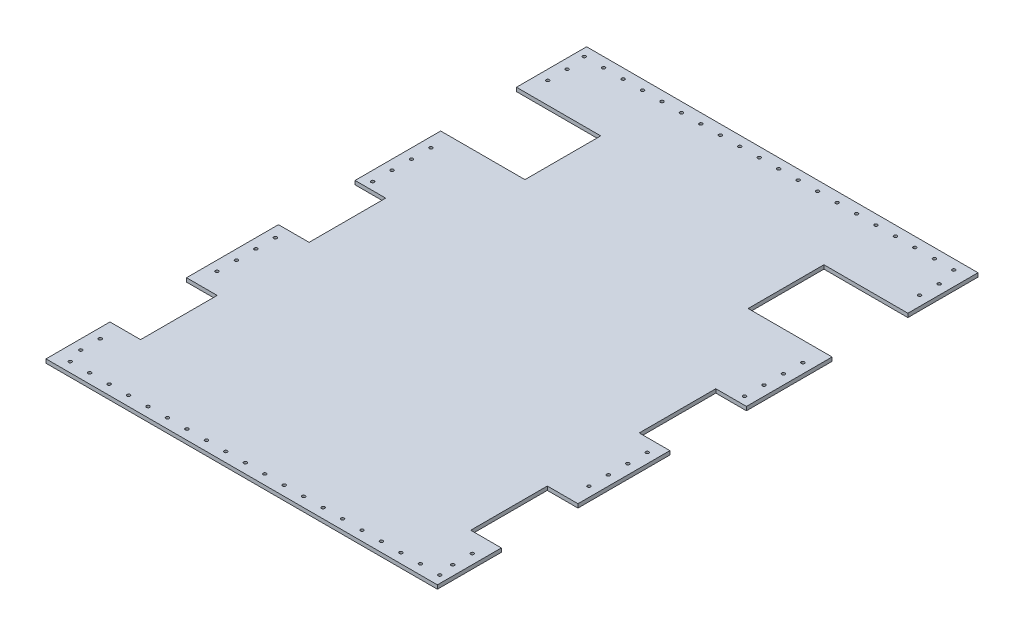
SolidWorks part; units mm, degrees
ref_plane "Alzado" through (0, 0, 0) normal (0, 0, 1) x (1, 0, 0)
ref_plane "Planta" through (0, 0, 0) normal (0, 1, 0) x (1, 0, 0)
ref_plane "Vista lateral" through (0, 0, 0) normal (1, 0, 0) x (0, 0, -1)
sketch "Croquis1" plane through (0, 0, 0) normal (0, 1, 0) x (1, 0, 0)
  line L1 (255.5, 352.9) -> (-255.5, 352.9)
  line L2 (255.5, 352.9) -> (255.5, -352.9)
  line L3 (255.5, -352.9) -> (-255.5, -352.9)
  line L4 (-255.5, 352.9) -> (-255.5, -352.9)
  line L5 (255.5, 352.9) -> (-255.5, -352.9) construction
  line L6 (255.5, -352.9) -> (-255.5, 352.9) construction
  point P0 (0, 0)
  dimension "D1" = 511
  dimension "D2" = 705.8
extrude "Saliente-Extruir1" add sketch "Croquis1" along normal blind 5
sketch "Croquis2" plane through (0, 0, 0) normal (0, -1, 0) x (-1, 0, 0)
  line L0 (255.5, 352.9) -> (255.5, -352.9) construction
  line L1 (255.5, -269.4013) -> (215.5, -269.4013)
  line L2 (255.5, -269.4013) -> (255.5, -169.4013)
  line L3 (255.5, -169.4013) -> (215.5, -169.4013)
  line L4 (215.5, -269.4013) -> (215.5, -169.4013)
  line L5 (-215.5, -269.4013) -> (-215.5, -169.4013)
  line L6 (-215.5, -269.4013) -> (-255.5, -269.4013)
  line L7 (-255.5, -269.4013) -> (-255.5, -169.4013)
  line L8 (-215.5, -169.4013) -> (-255.5, -169.4013)
  line L9 (255.5, -49.4013) -> (255.5, 50.5987)
  line L10 (255.5, -49.4013) -> (215.5, -49.4013)
  line L11 (215.5, -49.4013) -> (215.5, 50.5987)
  line L12 (255.5, 50.5987) -> (215.5, 50.5987)
  line L13 (-215.5, -49.4013) -> (-215.5, 50.5987)
  line L14 (-215.5, 50.5987) -> (-255.5, 50.5987)
  line L15 (-255.5, -49.4013) -> (-255.5, 50.5987)
  line L16 (-215.5, -49.4013) -> (-255.5, -49.4013)
  dimension "D1" = 40
  dimension "D2" = 100
  dimension "D3" = 2
  dimension "D4" = 2
extrude "Cortar-Extruir1" cut sketch "Croquis2" against normal blind 10
sketch "Croquis4" plane through (0, 0, 0) normal (0, -1, 0) x (-1, 0, 0)
  line L0 (255.5, 352.9) -> (255.5, 50.5987) construction
  line L1 (255.5, 162.4) -> (145.5, 162.4)
  line L2 (255.5, 162.4) -> (255.5, 261.3508)
  line L3 (255.5, 261.3508) -> (145.5, 261.3508)
  line L4 (145.5, 162.4) -> (145.5, 261.3508)
  line L5 (102.4913, 261.0642) -> (159.7413, 261.4458) construction
  line L6 (-145.9, 162.4) -> (-145.9, 261.3508)
  line L7 (-145.9, 162.4) -> (-255.9, 162.4)
  line L8 (-255.9, 162.4) -> (-255.9, 261.3508)
  line L9 (-145.9, 261.3508) -> (-255.9, 261.3508)
  dimension "D1" = 110
extrude "Cortar-Extruir3" cut sketch "Croquis4" against normal blind 10
sketch "Croquis7" plane through (0, 0, 0) normal (0, -1, 0) x (-1, 0, 0)
  circle A0 centre (236.6, -340.2) radius 2.07
  circle A1 centre (211.2, -340.2) radius 2.07
  circle A2 centre (185.8, -340.2) radius 2.07
  circle A3 centre (160.4, -340.2) radius 2.07
  circle A4 centre (135, -340.2) radius 2.07
  circle A5 centre (109.6, -340.2) radius 2.07
  circle A6 centre (84.2, -340.2) radius 2.07
  circle A7 centre (58.8, -340.2) radius 2.07
  circle A8 centre (33.4, -340.2) radius 2.07
  circle A9 centre (8, -340.2) radius 2.07
  circle A10 centre (-17.4, -340.2) radius 2.07
  circle A11 centre (-42.8, -340.2) radius 2.07
  circle A12 centre (-68.2, -340.2) radius 2.07
  circle A13 centre (-93.6, -340.2) radius 2.07
  circle A14 centre (-119, -340.2) radius 2.07
  circle A15 centre (-144.4, -340.2) radius 2.07
  circle A16 centre (-169.8, -340.2) radius 2.07
  circle A17 centre (-195.2, -340.2) radius 2.07
  circle A18 centre (-220.6, -340.2) radius 2.07
  circle A19 centre (-246, -340.2) radius 2.07
  circle A20 centre (242.8, -320.2) radius 2.07
  circle A21 centre (242.8, -294.8) radius 2.07
  circle A27 centre (242.8, -142.4) radius 2.07
  circle A28 centre (242.8, -117) radius 2.07
  circle A29 centre (242.8, -91.6) radius 2.07
  circle A30 centre (242.8, -66.2) radius 2.07
  circle A35 centre (242.8, 60.8) radius 2.07
  circle A36 centre (242.8, 86.2) radius 2.07
  circle A37 centre (242.8, 111.6) radius 2.07
  circle A38 centre (242.8, 137) radius 2.07
  circle A44 centre (242.8, 289.4) radius 2.07
  circle A45 centre (242.8, 314.8) radius 2.07
  circle A46 centre (242.8, -193.2) radius 2.07 [skipped]
  circle A47 centre (242.8, -218.6) radius 2.07 [skipped]
  circle A48 centre (242.8, -244) radius 2.07 [skipped]
  circle A49 centre (242.8, -269.4) radius 2.07 [skipped]
  circle A50 centre (242.8, -167.8) radius 2.07 [skipped]
  circle A51 centre (242.8, 35.4) radius 2.07 [skipped]
  circle A52 centre (242.8, 10) radius 2.07 [skipped]
  circle A53 centre (242.8, -15.4) radius 2.07 [skipped]
  circle A54 centre (242.8, -40.8) radius 2.07 [skipped]
  circle A55 centre (242.8, 238.6) radius 2.07 [skipped]
  circle A56 centre (242.8, 213.2) radius 2.07 [skipped]
  circle A57 centre (242.8, 187.8) radius 2.07 [skipped]
  circle A58 centre (242.8, 162.4) radius 2.07 [skipped]
  circle A59 centre (242.8, 264) radius 2.07 [skipped]
  dimension "D1" = 20
  dimension "D2" = 26
extrude "Cortar-Extruir6" cut sketch "Croquis7" against normal blind 10
sketch "Croquis8" plane through (0, 0, 0) normal (0, -1, 0) x (-1, 0, 0)
  circle A0 centre (246, 340.2) radius 2.07
  circle A1 centre (220.6, 340.2) radius 2.07
  circle A2 centre (195.2, 340.2) radius 2.07
  circle A3 centre (169.8, 340.2) radius 2.07
  circle A4 centre (144.4, 340.2) radius 2.07
  circle A5 centre (119, 340.2) radius 2.07
  circle A6 centre (93.6, 340.2) radius 2.07
  circle A7 centre (68.2, 340.2) radius 2.07
  circle A8 centre (42.8, 340.2) radius 2.07
  circle A9 centre (17.4, 340.2) radius 2.07
  circle A10 centre (-8, 340.2) radius 2.07
  circle A11 centre (-33.4, 340.2) radius 2.07
  circle A12 centre (-58.8, 340.2) radius 2.07
  circle A13 centre (-84.2, 340.2) radius 2.07
  circle A14 centre (-109.6, 340.2) radius 2.07
  circle A15 centre (-135, 340.2) radius 2.07
  circle A16 centre (-160.4, 340.2) radius 2.07
  circle A17 centre (-185.8, 340.2) radius 2.07
  circle A18 centre (-211.2, 340.2) radius 2.07
  circle A19 centre (-236.6, 340.2) radius 2.07
  circle A20 centre (-242.8, 314.8) radius 2.07
  circle A21 centre (-242.8, 289.4) radius 2.07
  circle A27 centre (-242.8, 137) radius 2.07
  circle A28 centre (-242.8, 111.6) radius 2.07
  circle A29 centre (-242.8, 86.2) radius 2.07
  circle A30 centre (-242.8, 60.8) radius 2.07
  circle A35 centre (-242.8, -66.2) radius 2.07
  circle A36 centre (-242.8, -91.6) radius 2.07
  circle A37 centre (-242.8, -117) radius 2.07
  circle A38 centre (-242.8, -142.4) radius 2.07
  circle A44 centre (-242.8, -294.8) radius 2.07
  circle A45 centre (-242.8, -320.2) radius 2.07
  circle A46 centre (-242.8, -269.4) radius 2.07 [skipped]
  circle A47 centre (-242.8, -244) radius 2.07 [skipped]
  circle A48 centre (-242.8, -218.6) radius 2.07 [skipped]
  circle A49 centre (-242.8, -193.2) radius 2.07 [skipped]
  circle A50 centre (-242.8, -167.8) radius 2.07 [skipped]
  circle A51 centre (-242.8, 238.6) radius 2.07 [skipped]
  circle A52 centre (-242.8, 213.2) radius 2.07 [skipped]
  circle A53 centre (-242.8, 162.4) radius 2.07 [skipped]
  circle A54 centre (-242.8, 187.8) radius 2.07 [skipped]
  circle A55 centre (-242.8, 264) radius 2.07 [skipped]
  circle A56 centre (-242.8, 35.4) radius 2.07 [skipped]
  circle A57 centre (-242.8, 10) radius 2.07 [skipped]
  circle A58 centre (-242.8, -15.4) radius 2.07 [skipped]
  circle A59 centre (-242.8, -40.8) radius 2.07 [skipped]
  dimension "D1" = 20
  dimension "D2" = 26
extrude "Cortar-Extruir7" cut sketch "Croquis8" against normal blind 10
